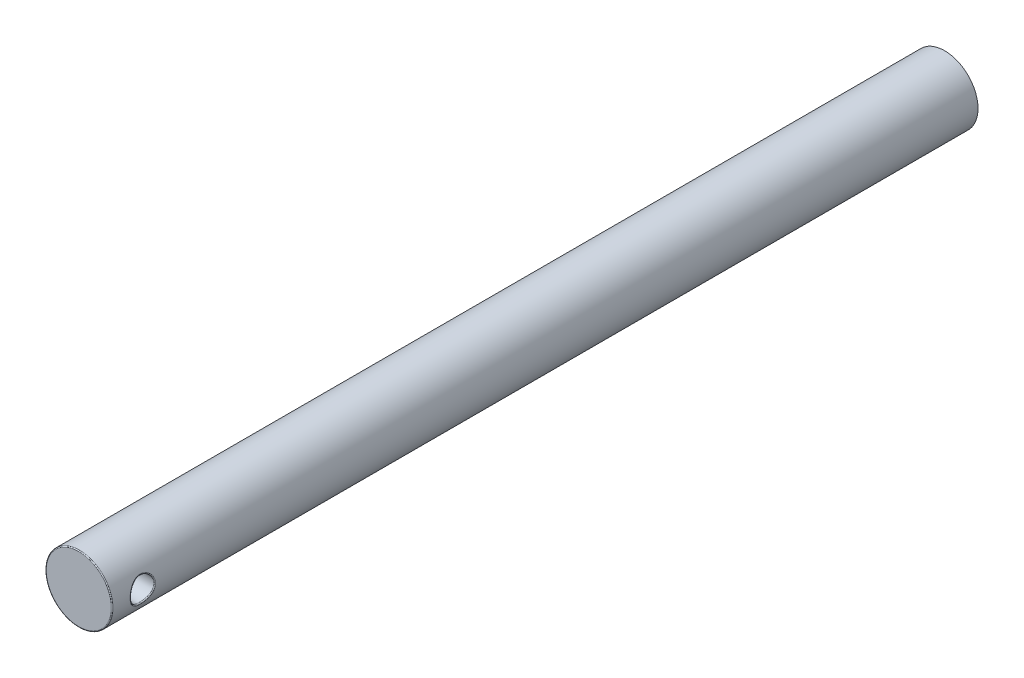
SolidWorks part; units mm, degrees
ref_plane "Front Plane" through (0, 0, 0) normal (0, 0, 1) x (1, 0, 0)
ref_plane "Top Plane" through (0, 0, 0) normal (0, 1, 0) x (1, 0, 0)
ref_plane "Right Plane" through (0, 0, 0) normal (1, 0, 0) x (0, 0, -1)
sketch "Sketch1" plane through (0, 0, 0) normal (0, 0, 1) x (1, 0, 0)
  circle A2 centre (20.0025, 19.685) radius 9.779
  circle A3 centre (20.0025, 19.685) radius 9.779
  dimension "D1" = 0.254
extrude "Boss-Extrude1" add sketch "Sketch1" along normal blind 254
sketch "Sketch2" plane through (0, 0, 0) normal (1, 0, 0) x (0, 0, -1)
  line L0 (-254, 19.685) -> (7.8089, 19.685) construction
  line L1 (-254, 29.464) -> (-254, 9.906) construction
  circle A0 centre (-244.983, 19.685) radius 3.4925
  dimension "D1" = 6.985
  dimension "D2" = 9.017
extrude "Cut-Extrude1" cut sketch "Sketch2" along normal through all contours A0
fillet "Fillet1" radius 0.254 2 edges at (10.2398, 19.1211, 241.5363) (29.7652, 20.2489, 241.5363)
fillet "Fillet2" radius 0.254 1 edges at (29.7815, 19.685, 254)
